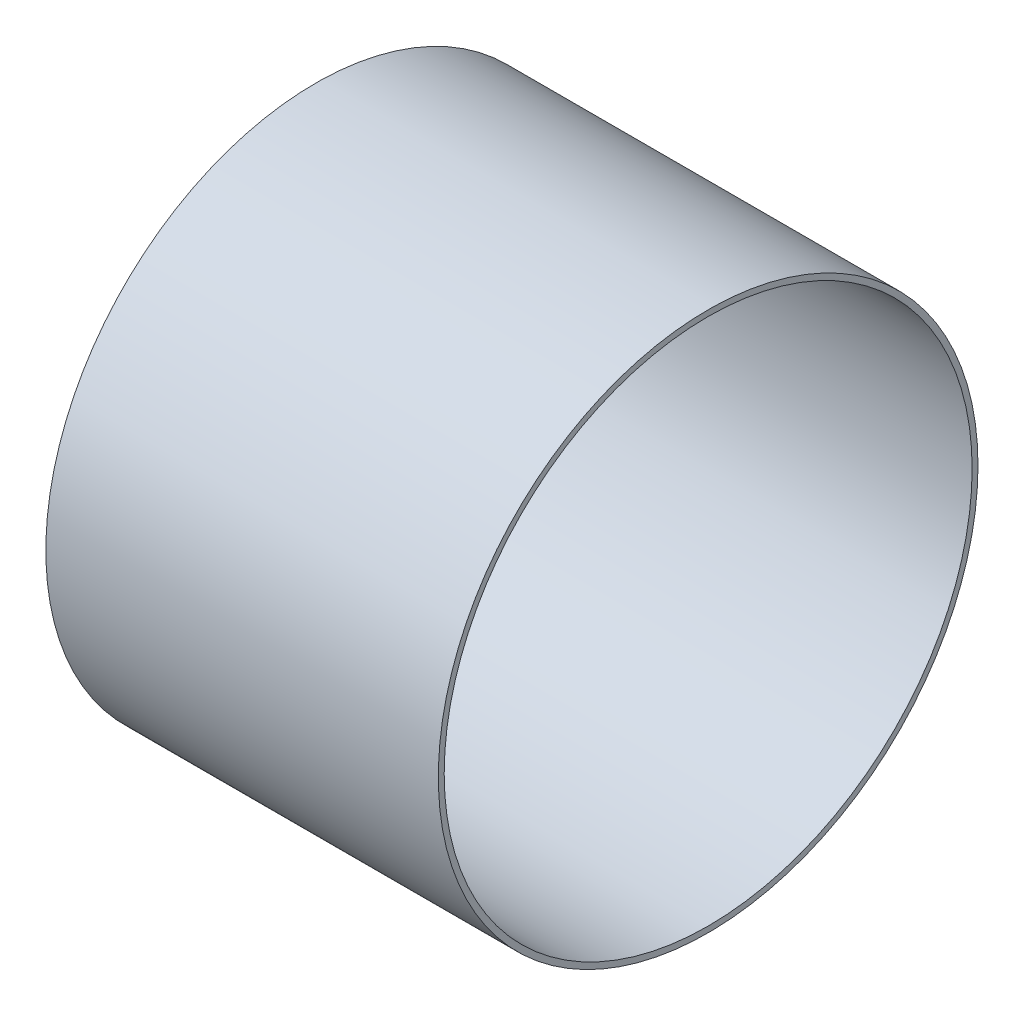
SolidWorks part; units mm, degrees
material "AISI 316 Annealed Stainless Steel Bar (SS)"
ref_plane "Front Plane" through (0, 0, 0) normal (0, 0, 1) x (1, 0, 0)
ref_plane "Top Plane" through (0, 0, 0) normal (0, 1, 0) x (1, 0, 0)
ref_plane "Right Plane" through (0, 0, 0) normal (1, 0, 0) x (0, 0, -1)
sketch "Sketch1" plane through (0, 0, 0) normal (1, 0, 0) x (0, 0, -1)
  circle A0 centre (0, 0) radius 69.85
  circle A1 centre (0, 0) radius 68.3311
  dimension "D1" = 1.5189
  dimension "D2" = 139.7
extrude "Boss-Extrude1" add sketch "Sketch1" along normal blind 101.6
